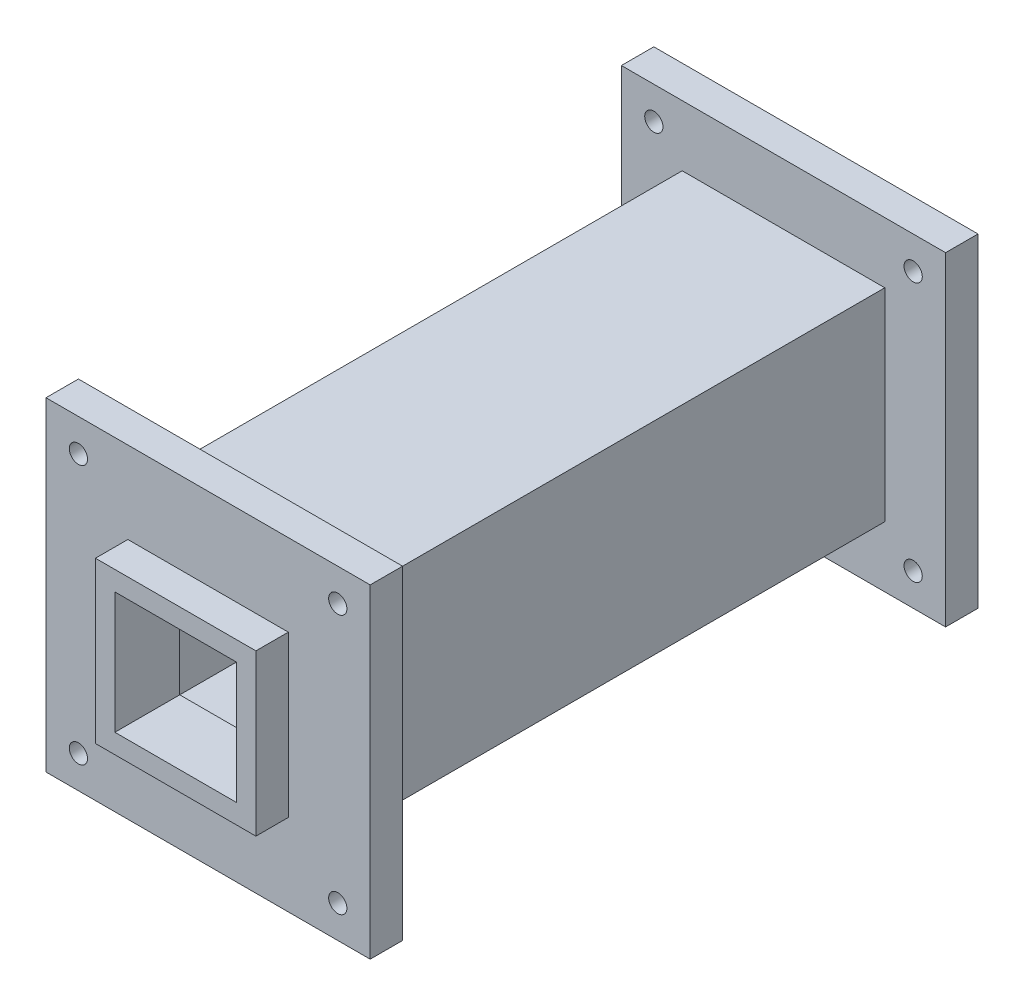
SolidWorks part; units mm, degrees
ref_plane "前视基准面" through (0, 0, 0) normal (0, 0, 1) x (1, 0, 0)
ref_plane "上视基准面" through (0, 0, 0) normal (0, 1, 0) x (1, 0, 0)
ref_plane "右视基准面" through (0, 0, 0) normal (1, 0, 0) x (0, 0, -1)
other "Configuration Table"
sketch "草图1" plane through (0, 0, 0) normal (0, 0, 1) x (1, 0, 0)
  line L1 (-25, -25) -> (25, -25)
  line L2 (-25, -25) -> (-25, 25)
  line L3 (-25, 25) -> (25, 25)
  line L4 (25, -25) -> (25, 25)
  line L6 (-20.2, -20.2) -> (20.2, -20.2)
  line L7 (-20.2, -20.2) -> (-20.2, 20.2)
  line L8 (-20.2, 20.2) -> (20.2, 20.2)
  line L9 (20.2, -20.2) -> (20.2, 20.2)
extrude "50方管壁厚4p8" add sketch "草图1" along normal blind 150
sketch "草图2" plane through (0, 0, 0) normal (0, 0, 1) x (1, 0, 0)
  line L1 (-40, -40) -> (40, -40)
  line L2 (-40, -40) -> (-40, 40)
  line L3 (-40, 40) -> (40, 40)
  line L4 (40, -40) -> (40, 40)
  line L6 (-20.2, -20.2) -> (20.2, -20.2)
  line L7 (-20.2, -20.2) -> (-20.2, 20.2)
  line L8 (-20.2, 20.2) -> (20.2, 20.2)
  line L9 (20.2, -20.2) -> (20.2, 20.2)
extrude "下连接法兰" add sketch "草图2" along normal blind 8
sketch "草图3" plane through (0, 0, 0) normal (0, 0, 1) x (1, 0, 0)
  line L1 (-40, -40) -> (40, -40)
  line L2 (-40, -40) -> (-40, 40)
  line L3 (-40, 40) -> (40, 40)
  line L4 (40, -40) -> (40, 40)
  line L6 (-15, -15) -> (15, -15)
  line L7 (-15, -15) -> (-15, 15)
  line L8 (-15, 15) -> (15, 15)
  line L9 (15, -15) -> (15, 15)
extrude "上连接法兰与承台" add sketch "草图3" along normal blind 8 from offset 142
sketch "草图4" plane through (0, 0, 0) normal (0, 0, 1) x (1, 0, 0)
  line L1 (-19.8, -19.8) -> (19.8, -19.8)
  line L2 (-19.8, -19.8) -> (-19.8, 19.8)
  line L3 (-19.8, 19.8) -> (19.8, 19.8)
  line L4 (19.8, -19.8) -> (19.8, 19.8)
  line L6 (-15, -15) -> (15, -15)
  line L7 (-15, -15) -> (-15, 15)
  line L8 (-15, 15) -> (15, 15)
  line L9 (15, -15) -> (15, 15)
extrude "定位凸台39p6" add sketch "草图4" along normal blind 8 from offset 150
sketch "草图5" plane through (0, 0, 0) normal (0, 0, 1) x (1, 0, 0)
  circle A0 centre (-32, -32) radius 2.25
  circle A1 centre (-32, 32) radius 2.25
  circle A2 centre (32, -32) radius 2.25
  circle A3 centre (32, 32) radius 2.25
extrude "四个M4法兰通孔" cut sketch "草图5" against normal through all and the other way through all
